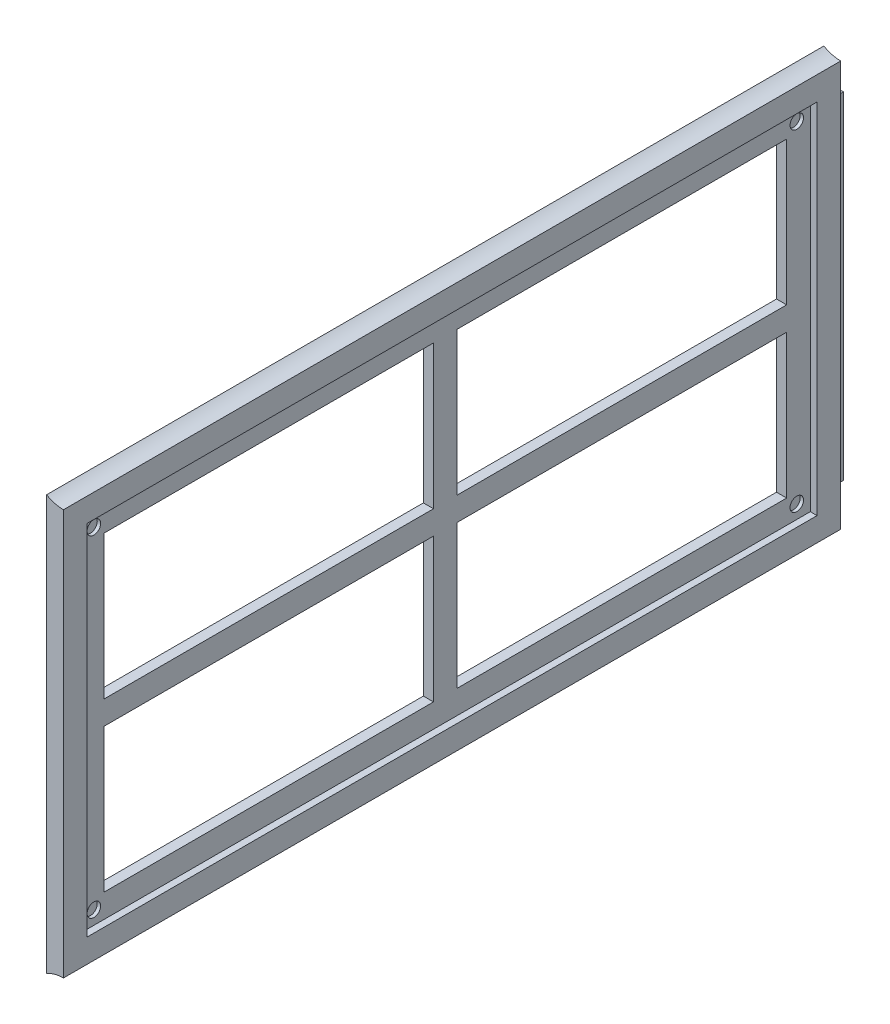
SolidWorks part; units mm, degrees
ref_plane "Plano frontal" through (0, 0, 0) normal (0, 0, 1) x (1, 0, 0)
ref_plane "Plano superior" through (0, 0, 0) normal (0, 1, 0) x (1, 0, 0)
ref_plane "Plano direito" through (0, 0, 0) normal (1, 0, 0) x (0, 0, -1)
sketch "Esboço1" plane through (0, 0, 0) normal (0, 0, 1) x (1, 0, 0)
  line L0 (-2.7, -61.3397) -> (-2.7, 61.3397)
  line L1 (2.3, 60.002) -> (2.3, -60.002)
  line L2 (-1, 50) -> (0.6, 50)
  line L3 (-1, 50) -> (-1, -49.6)
  line L4 (-1, -49.6) -> (0.6, -49.6)
  line L5 (0.6, 50) -> (0.6, -49.6)
  arc A0 (-2.7, 61.3397) -> (2.3, 60.002) centre (2.2965, 70.002) ccw
  arc A1 (-2.7, -61.3397) -> (2.3, -60.002) centre (2.2965, -70.002) cw
  dimension "D1" = 122.6795
  dimension "D2" = 1.6
  dimension "D3" = 99.6
  dimension "D4" = 1.7
  dimension "D5" = 1.7
extrude "Ressalto-extrusão1" add sketch "Esboço1" along normal blind 230
sketch "Esboço2" plane through (0, 0, 230) normal (0, 0, 1) x (1, 0, 0)
  line L1 (-1, 50) -> (0.6, 50)
  line L2 (-1, 50) -> (-1, -49.6)
  line L3 (-1, -49.6) -> (0.6, -49.6)
  line L4 (0.6, 50) -> (0.6, -49.6)
extrude "Ressalto-extrusão2" add sketch "Esboço2" against normal blind 232.5
sketch "Esboço3" plane through (2.3, 0, 0) normal (1, 0, 0) x (0, 0, -1)
  line L0 (-230, 60.002) -> (0, 60.002) construction
  line L1 (-223, 53.002) -> (-7, 53.002)
  line L2 (-223, 53.002) -> (-223, -53.002)
  line L3 (-223, -53.002) -> (-7, -53.002)
  line L4 (-7, 53.002) -> (-7, -53.002)
  line L5 (-230, -60.002) -> (-230, 60.002) construction
  line L6 (-230, -60.002) -> (0, -60.002) construction
  line L7 (0, -49.6) -> (0, 50) construction
  dimension "D1" = 7
  dimension "D2" = 7
  dimension "D3" = 7
  dimension "D4" = 7
sketch "Esboço4" plane through (2.3, 0, 0) normal (1, 0, 0) x (0, 0, -1)
  line L0 (-223, 53.002) -> (-7, 53.002) construction
  line L1 (-216, 46.002) -> (-14, 46.002)
  line L2 (-216, 46.002) -> (-216, -46.002)
  line L3 (-216, -46.002) -> (-14, -46.002)
  line L4 (-14, 46.002) -> (-14, -46.002)
  line L5 (-223, 53.002) -> (-223, -53.002) construction
  line L6 (-223, -53.002) -> (-7, -53.002) construction
  line L7 (-7, 53.002) -> (-7, -53.002) construction
  line L8 (-216, -46.002) -> (-14, -46.002) construction
  line L9 (-14, -46.002) -> (-14, 46.002) construction
  line L10 (-115, 46.002) -> (-115, -46.002) construction
  line L11 (-216, 0) -> (-14, 0) construction
  line L13 (-216, 3.5) -> (-14, 3.5)
  line L14 (-216, 3.5) -> (-216, -3.5)
  line L15 (-216, -3.5) -> (-14, -3.5)
  line L16 (-14, 3.5) -> (-14, -3.5)
  line L17 (-216, 3.5) -> (-14, -3.5) construction
  line L18 (-216, -3.5) -> (-14, 3.5) construction
  line L19 (-118.5, 46.002) -> (-111.5, 46.002)
  line L20 (-118.5, 46.002) -> (-118.5, -46.002)
  line L21 (-118.5, -46.002) -> (-111.5, -46.002)
  line L22 (-111.5, 46.002) -> (-111.5, -46.002)
  line L23 (-118.5, 46.002) -> (-111.5, -46.002) construction
  line L24 (-118.5, -46.002) -> (-111.5, 46.002) construction
  line L25 (-216, 46.002) -> (-118.5, 46.002)
  line L26 (-216, 46.002) -> (-216, 3.5)
  line L27 (-216, 3.5) -> (-118.5, 3.5)
  line L28 (-118.5, 46.002) -> (-118.5, 3.5)
  line L29 (-111.5, 46.002) -> (-14, 46.002)
  line L30 (-111.5, 46.002) -> (-111.5, 3.5)
  line L31 (-111.5, 3.5) -> (-14, 3.5)
  line L32 (-14, 46.002) -> (-14, 3.5)
  point P16 (-115, 0)
  point P21 (-115, 0)
  dimension "D1" = 7
  dimension "D2" = 7
  dimension "D3" = 7
  dimension "D4" = 7
  dimension "D5" = 7
  dimension "D6" = 7
sketch "Esboço5" plane through (2.3, 0, 0) normal (1, 0, 0) x (0, 0, -1)
  line L1 (-216, 46.002) -> (-118.5, 46.002)
  line L2 (-216, 46.002) -> (-216, 3.5)
  line L3 (-216, 3.5) -> (-118.5, 3.5)
  line L4 (-118.5, 46.002) -> (-118.5, 3.5)
  line L5 (-111.5, 46.002) -> (-14, 46.002)
  line L6 (-111.5, 46.002) -> (-111.5, 3.5)
  line L7 (-111.5, 3.5) -> (-14, 3.5)
  line L8 (-14, 46.002) -> (-14, 3.5)
  line L9 (-216, -3.5) -> (-118.5, -3.5)
  line L10 (-216, -3.5) -> (-216, -46.002)
  line L11 (-216, -46.002) -> (-118.5, -46.002)
  line L12 (-118.5, -3.5) -> (-118.5, -46.002)
  line L13 (-14, -3.5) -> (-111.5, -3.5)
  line L14 (-14, -3.5) -> (-14, -46.002)
  line L15 (-14, -46.002) -> (-111.5, -46.002)
  line L16 (-111.5, -3.5) -> (-111.5, -46.002)
extrude "Corte-extrusão1" cut sketch "Esboço5" against normal blind 230
extrude "Corte-extrusão2" cut sketch "Esboço3" against normal blind 2
sketch "Esboço7" plane through (0.3, 0, 0) normal (1, 0, 0) x (0, 0, -1)
  line L1 (-223, 53.002) -> (-7, 53.002)
  line L2 (-223, 53.002) -> (-223, -53.002)
  line L3 (-223, -53.002) -> (-7, -53.002)
  line L4 (-7, 53.002) -> (-7, -53.002)
  line L5 (-216, 46.002) -> (-118.5, 46.002)
  line L6 (-216, 46.002) -> (-216, 3.5)
  line L7 (-216, 3.5) -> (-118.5, 3.5)
  line L8 (-118.5, 46.002) -> (-118.5, 3.5)
  line L9 (-111.5, 46.002) -> (-14, 46.002)
  line L10 (-111.5, 46.002) -> (-111.5, 3.5)
  line L11 (-111.5, 3.5) -> (-14, 3.5)
  line L12 (-14, 46.002) -> (-14, 3.5)
  line L13 (-111.5, -3.5) -> (-14, -3.5)
  line L14 (-111.5, -3.5) -> (-111.5, -46.002)
  line L15 (-111.5, -46.002) -> (-14, -46.002)
  line L16 (-14, -3.5) -> (-14, -46.002)
  line L17 (-118.5, -46.002) -> (-216, -46.002)
  line L18 (-118.5, -46.002) -> (-118.5, -3.5)
  line L19 (-118.5, -3.5) -> (-216, -3.5)
  line L20 (-216, -46.002) -> (-216, -3.5)
sketch "Esboço8" plane through (0.3, 0, 0) normal (1, 0, 0) x (0, 0, -1)
  circle A0 centre (-219, 49) radius 2
  circle A1 centre (-11, 49) radius 2
  circle A2 centre (-11, -49) radius 2
  circle A3 centre (-219, -49) radius 2
extrude "Corte-extrusão3" cut sketch "Esboço8" against normal blind 1
